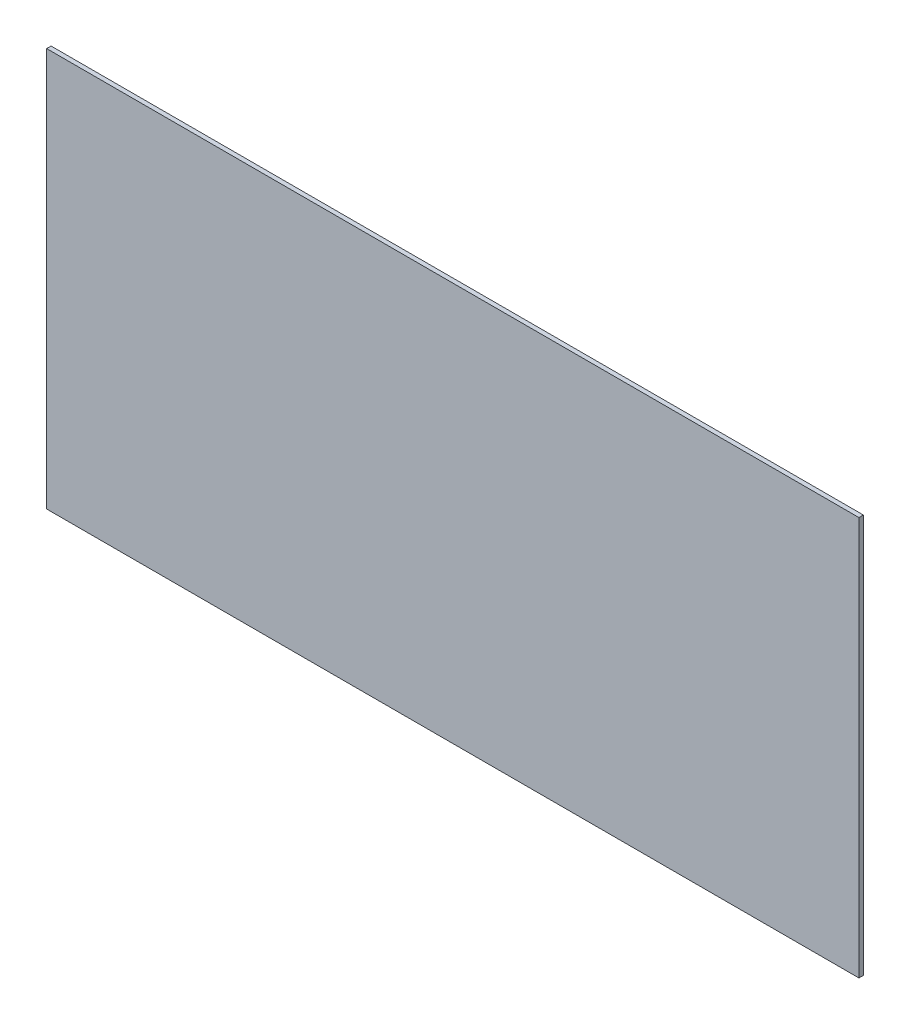
SolidWorks part; units mm, degrees
ref_plane "Front Plane" through (0, 0, 0) normal (0, 0, 1) x (1, 0, 0)
ref_plane "Top Plane" through (0, 0, 0) normal (0, 1, 0) x (1, 0, 0)
ref_plane "Right Plane" through (0, 0, 0) normal (1, 0, 0) x (0, 0, -1)
sketch "Sketch1" plane through (0, 0, 0) normal (0, 0, 1) x (1, 0, 0)
  line L1 (-275, -135) -> (275, -135)
  line L2 (-275, -135) -> (-275, 135)
  line L3 (-275, 135) -> (275, 135)
  line L4 (275, -135) -> (275, 135)
  line L5 (-275, -135) -> (275, 135) construction
  line L6 (-275, 135) -> (275, -135) construction
  point P0 (0, 0)
  dimension "D1" = 550
  dimension "D2" = 270
extrude "Boss-Extrude1" add sketch "Sketch1" along normal blind 3
